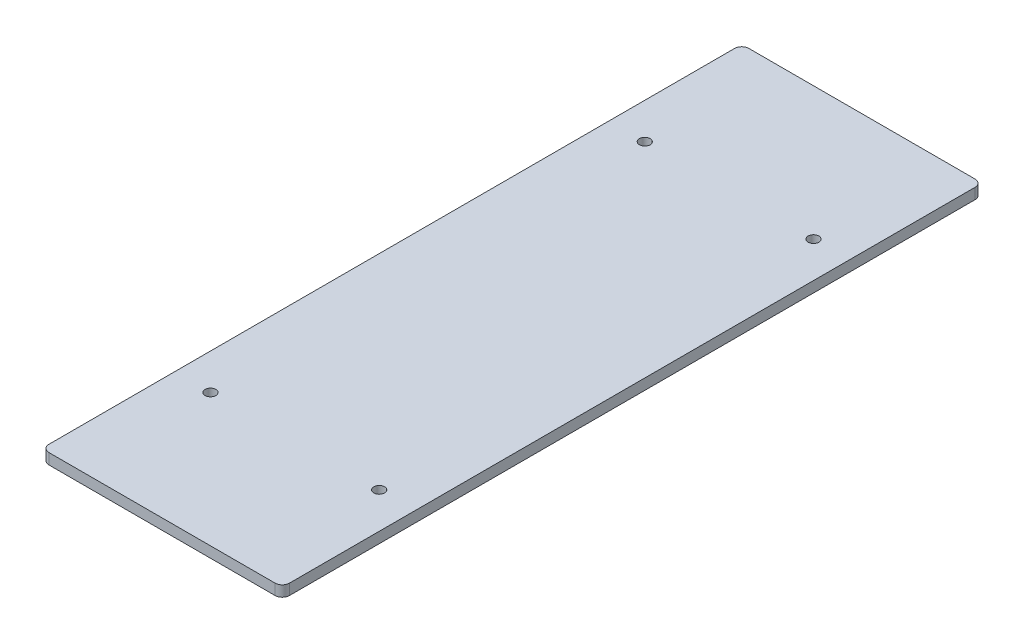
SolidWorks part; units mm, degrees
ref_plane "Front Plane" through (0, 0, 0) normal (0, 0, 1) x (1, 0, 0)
ref_plane "Top Plane" through (0, 0, 0) normal (0, 1, 0) x (1, 0, 0)
ref_plane "Right Plane" through (0, 0, 0) normal (1, 0, 0) x (0, 0, -1)
sketch "Sketch1" plane through (0, 0, 0) normal (0, 1, 0) x (1, 0, 0)
  line L1 (-33.5, 97.5) -> (33.5, 97.5)
  line L2 (-33.5, 97.5) -> (-33.5, -97.5)
  line L3 (-33.5, -97.5) -> (33.5, -97.5)
  line L4 (33.5, 97.5) -> (33.5, -97.5)
  line L5 (-33.5, 97.5) -> (33.5, -97.5) construction
  line L6 (-33.5, -97.5) -> (33.5, 97.5) construction
  point P0 (0, 0)
  dimension "D1" = 195
  dimension "D2" = 67
extrude "Boss-Extrude1" add sketch "Sketch1" along normal blind 3
sketch "Sketch2" plane through (0, 3, 0) normal (0, 1, 0) x (1, 0, 0)
  line L0 (-33.5, 0) -> (34.1652, 0) construction
  line L1 (-33.5, 97.5) -> (-33.5, -97.5) construction
  line L2 (0, 97.5) -> (0, -97.5) construction
  line L3 (33.5, 97.5) -> (-33.5, 97.5) construction
  line L4 (-33.5, -97.5) -> (33.5, -97.5) construction
  line L6 (-33.5, -70.5) -> (33.5, -70.5)
  line L7 (-33.5, -70.5) -> (-33.5, 70.5)
  line L8 (-33.5, 70.5) -> (33.5, 70.5)
  line L9 (33.5, -70.5) -> (33.5, 70.5)
  line L10 (-33.5, -70.5) -> (33.5, 70.5) construction
  line L11 (-33.5, 70.5) -> (33.5, -70.5) construction
  circle A0 centre (-23.5, -60.5) radius 1.5
  circle A1 centre (23.5, -60.5) radius 1.5
  circle A2 centre (23.5, 60.5) radius 1.5
  circle A3 centre (-23.5, 60.5) radius 1.5
  point P11 (0, 0)
  point P24 (0, 0)
  dimension "D3" = 3
  dimension "D1" = 141
  dimension "D2" = 67
  dimension "D4" = 10
  dimension "D5" = 10
extrude "Cut-Extrude1" cut sketch "Sketch2" against normal blind 3 contours A3 | A2 | A0 | A1
fillet "Fillet1" radius 2 4 edges at (33.5, 1.5, -97.5) (33.5, 1.5, 97.5) (-33.5, 1.5, 97.5) (-33.5, 1.5, -97.5)
